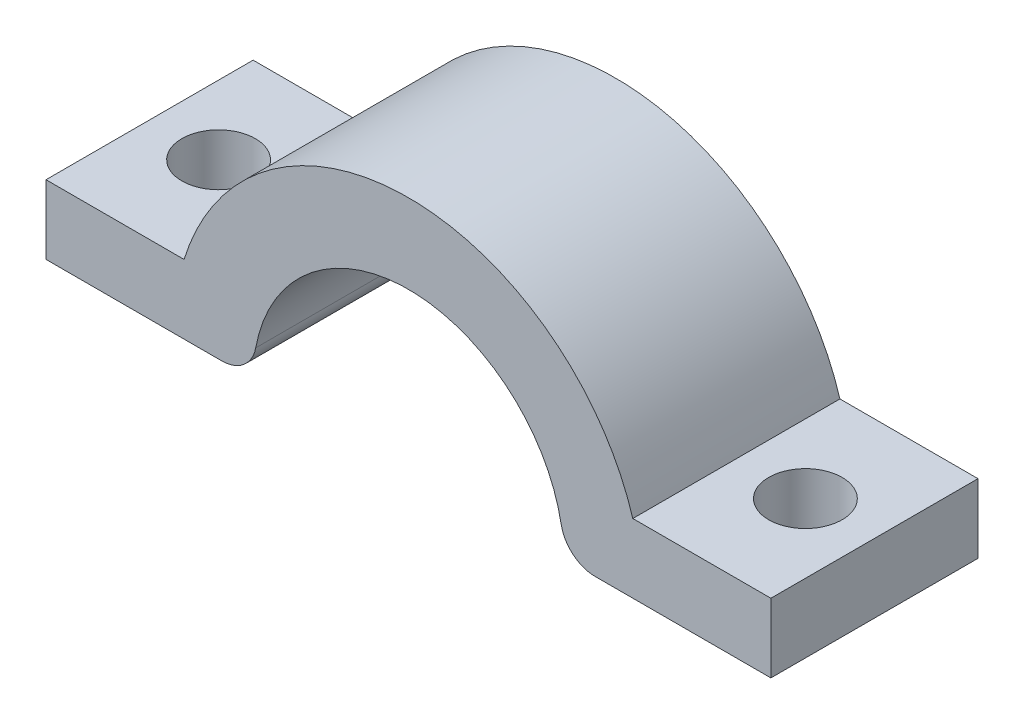
SolidWorks part; units mm, degrees
ref_plane "Front Plane" through (0, 0, 0) normal (0, 0, 1) x (1, 0, 0)
ref_plane "Top Plane" through (0, 0, 0) normal (0, 1, 0) x (1, 0, 0)
ref_plane "Right Plane" through (0, 0, 0) normal (1, 0, 0) x (0, 0, -1)
sketch "Sketch1" plane through (0, 0, 0) normal (0, 0, 1) x (1, 0, 0)
  line L0 (14.2875, 0) -> (33.3375, 0)
  line L1 (33.3375, 0) -> (33.3375, 6.35)
  line L2 (33.3375, 6.35) -> (20.6375, 6.35)
  line L3 (0, 21.5923) -> (0, 14.2875) construction
  line L4 (-33.3375, 6.35) -> (-20.6375, 6.35)
  line L5 (-33.3375, 0) -> (-33.3375, 6.35)
  line L6 (-14.2875, 0) -> (-33.3375, 0)
  arc A0 (-14.2875, 0) -> (14.2875, 0) centre (0, 0) cw
  arc A1 (20.6375, 6.35) -> (-20.6375, 6.35) centre (0, 0) ccw
  point P12 (0, 0)
  point P13 (0, 0)
  dimension "D1" = 12.7
  dimension "D2" = 19.05
  dimension "D3" = 6.35
  dimension "D4" = 14.2875
extrude "Boss-Extrude1" add sketch "Sketch1" along normal blind 19.05
sketch "Sketch2" plane through (0, 6.35, 0) normal (0, 1, 0) x (1, 0, 0)
  line L0 (-20.6375, -19.05) -> (-33.3375, -19.05) construction
  line L1 (-33.3375, -19.05) -> (-33.3375, 0) construction
  line L2 (33.3375, -19.05) -> (33.3375, 0) construction
  line L3 (33.3375, 0) -> (20.6375, 0) construction
  circle A0 centre (26.9875, -9.525) radius 3.3782
  circle A1 centre (-26.9875, -9.525) radius 3.3782
  point P6 (-26.9875, -19.05)
  point P9 (-33.3375, -9.525)
  point P12 (33.3375, -9.525)
  point P15 (26.9875, 0)
  dimension "D1" = 6.7564
  dimension "D2" = 6.7564
extrude "Cut-Extrude1" cut sketch "Sketch2" against normal through all
fillet "Fillet1" radius 3.175 2 edges at (-14.2875, 0, 9.525) (14.2875, 0, 9.525)
